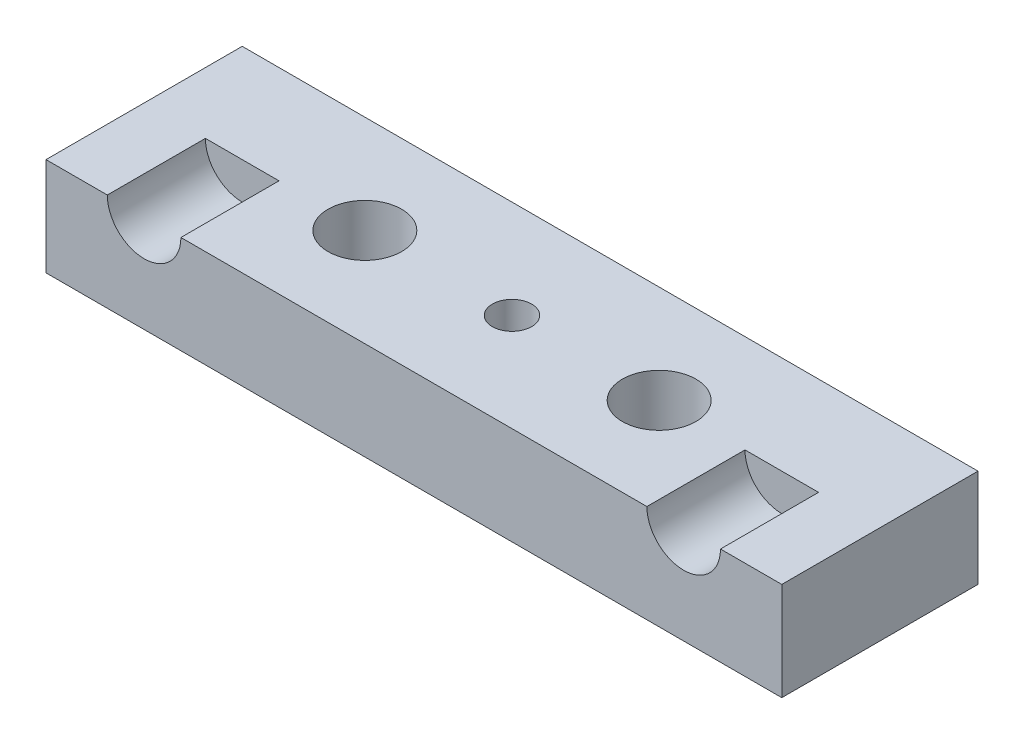
SolidWorks part; units mm, degrees
ref_plane "Alzado" through (0, 0, 0) normal (0, 0, 1) x (1, 0, 0)
ref_plane "Planta" through (0, 0, 0) normal (0, 1, 0) x (1, 0, 0)
ref_plane "Vista lateral" through (0, 0, 0) normal (1, 0, 0) x (0, 0, -1)
sketch "Croquis1" plane through (0, 0, 0) normal (0, 1, 0) x (1, 0, 0)
  line L1 (75, -20) -> (-75, -20)
  line L2 (75, -20) -> (75, 20)
  line L3 (75, 20) -> (-75, 20)
  line L4 (-75, -20) -> (-75, 20)
  line L5 (75, -20) -> (-75, 20) construction
  line L6 (75, 20) -> (-75, -20) construction
  point P0 (0, 0)
  dimension "D1" = 40
  dimension "D2" = 150
extrude "Extruir1" add sketch "Croquis1" along normal blind 20
sketch "Croquis4" plane through (0, 20, 0) normal (0, 1, 0) x (1, 0, 0)
  line L0 (0, 0) -> (-75, 0) construction
  line L1 (-75, 20) -> (-75, -20) construction
  line L2 (0, 0) -> (0, 20) construction
  line L3 (75, 20) -> (-75, 20) construction
  circle A0 centre (-30, 0) radius 7.5
  circle A1 centre (30, 0) radius 7.5
  circle A2 centre (0, 0) radius 4
  dimension "D1" = 30
  dimension "D2" = 15
  dimension "D3" = 8
extrude "Extruir3" cut sketch "Croquis4" against normal through all
sketch "Croquis5" plane through (0, 0, 20) normal (0, 0, 1) x (1, 0, 0)
  line L0 (-75, 10) -> (75, 10) construction
  line L1 (-75, 20) -> (-75, 0) construction
  line L2 (75, 20) -> (75, 0) construction
  line L3 (0, 0) -> (0, 10) construction
  line L4 (-75, 20) -> (75, 20) construction
  circle A0 centre (-55, 20) radius 7.5
  circle A1 centre (55, 20) radius 7.5
  dimension "D1" = 15
  dimension "D2" = 20
extrude "Extruir4" cut sketch "Croquis5" against normal blind 20
